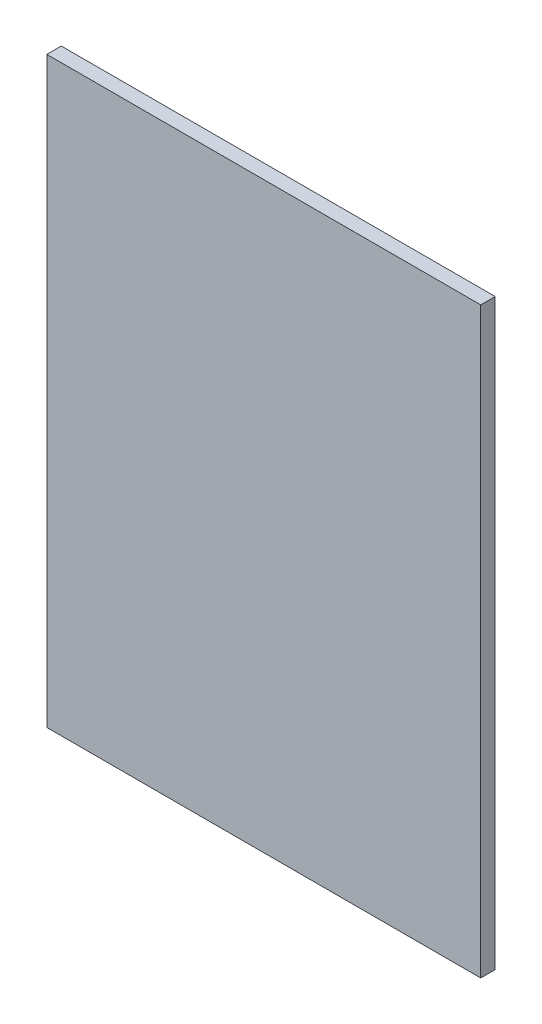
SolidWorks part; units mm, degrees
ref_plane "Front" through (0, 0, 0) normal (0, 0, 1) x (1, 0, 0)
ref_plane "Top" through (0, 0, 0) normal (0, 1, 0) x (1, 0, 0)
ref_plane "Right" through (0, 0, 0) normal (1, 0, 0) x (0, 0, -1)
sketch "Sketch1" plane through (0, 0, 0) normal (0, 0, 1) x (1, 0, 0)
  line L1 (-38.1, 51.181) -> (38.1, 51.181)
  line L2 (-38.1, 51.181) -> (-38.1, -51.181)
  line L3 (-38.1, -51.181) -> (38.1, -51.181)
  line L4 (38.1, 51.181) -> (38.1, -51.181)
  point P4 (-38.1, 0)
  point P7 (0, 51.181)
  dimension "D1" = 76.2
  dimension "D2" = 102.362
extrude "Boss-Extrude1" add sketch "Sketch1" along normal blind 2.54
